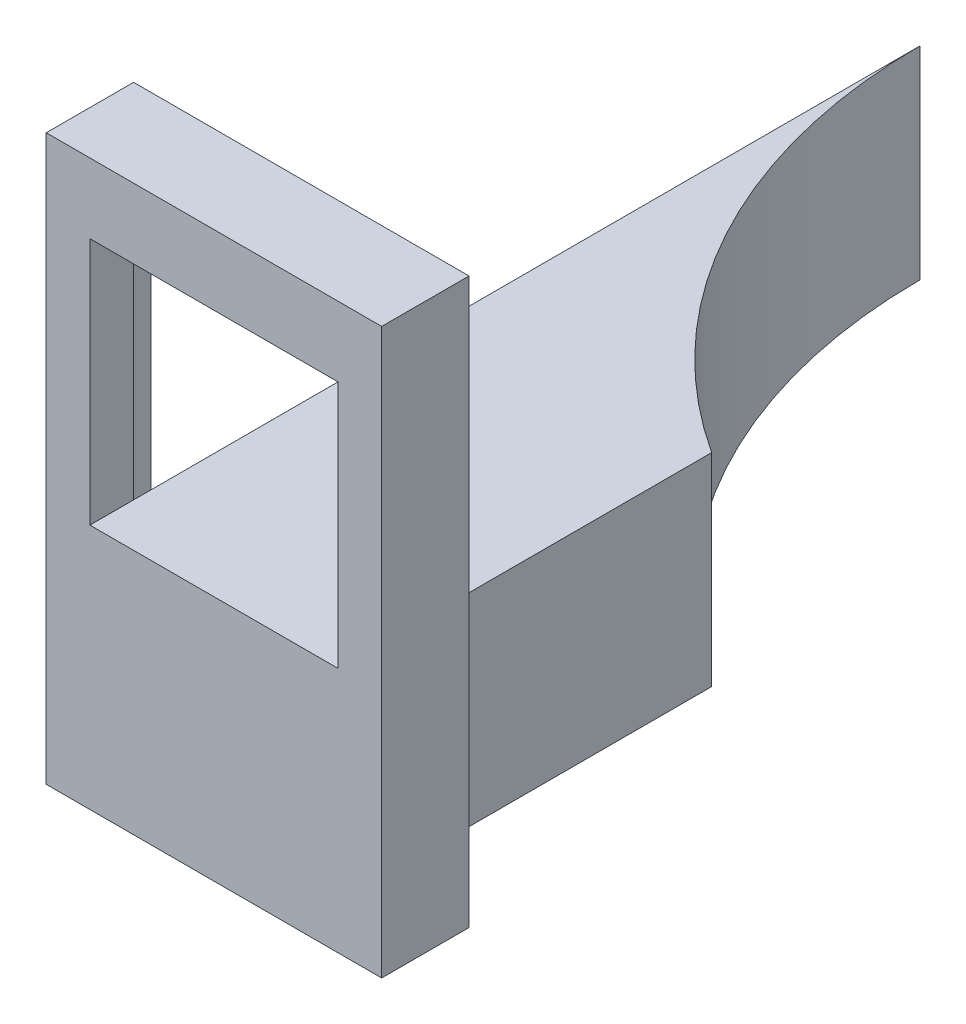
SolidWorks part; units mm, degrees
ref_plane "정면" through (0, 0, 0) normal (0, 0, 1) x (1, 0, 0)
ref_plane "윗면" through (0, 0, 0) normal (0, 1, 0) x (1, 0, 0)
ref_plane "우측면" through (0, 0, 0) normal (1, 0, 0) x (0, 0, -1)
sketch "스케치8" plane through (0, 0, 0) normal (0, 0, 1) x (1, 0, 0)
  line L0 (0, 60.6) -> (0, 0)
  line L1 (0, 0) -> (34.4, 0)
  line L2 (34.4, 0) -> (34.4, 60.6)
  line L3 (34.4, 60.6) -> (0, 60.6)
  line L4 (3, 54.6) -> (3, 3)
  line L5 (3, 3) -> (31.4, 3)
  line L6 (31.4, 3) -> (31.4, 54.6)
  line L7 (31.4, 54.6) -> (3, 54.6)
  dimension "D1" = 6
  dimension "D2" = 3
  dimension "D3" = 3
  dimension "D4" = 3
  dimension "D5" = 60.6
  dimension "D6" = 34.4
extrude "보스-돌출4" add sketch "스케치8" against normal blind 5
sketch "스케치9" plane through (0, 0, 0) normal (0, 0, 1) x (1, 0, 0)
  line L0 (31.4, 3) -> (31.4, 54.6) construction
  line L1 (3, 3) -> (31.4, 3)
  line L2 (3, 3) -> (3, 26.2)
  line L3 (3, 26.2) -> (31.4, 26.2)
  line L4 (31.4, 3) -> (31.4, 26.2)
  line L5 (31.4, 54.6) -> (3, 54.6) construction
  dimension "D1" = 28.4
extrude "보스-돌출5" add sketch "스케치9" against normal blind 95
sketch "스케치10" plane through (0, 26.2, 0) normal (0, 1, 0) x (1, 0, 0)
  circle A0 centre (65.2, 95) radius 62.2
  dimension "D1" = 124.4
extrude "컷-돌출3" cut sketch "스케치10" against normal blind 100
ref_plane "평면1" through (31.4, 26.2, -42.7851) normal (0, 0, 1) x (1, 0, 0)
sketch "스케치13" plane through (0, 0, 0) normal (0, 0, 1) x (1, 0, 0)
  line L0 (0, 60.6) -> (0, 0) construction
  line L1 (-2, -2) -> (36.4, -2)
  line L2 (-2, -2) -> (-2, 62.6)
  line L3 (-2, 62.6) -> (36.4, 62.6)
  line L4 (36.4, -2) -> (36.4, 62.6)
  line L5 (34.4, 0) -> (34.4, 60.6) construction
  line L6 (34.4, 60.6) -> (0, 60.6) construction
  line L7 (0, 0) -> (34.4, 0) construction
  line L8 (0, 0) -> (34.4, 0)
  line L9 (34.4, 0) -> (34.4, 60.6)
  line L10 (0, 60.6) -> (0, 0)
  line L11 (34.4, 60.6) -> (0, 60.6)
  dimension "D1" = 2
  dimension "D2" = 2
  dimension "D3" = 2
  dimension "D4" = 2
extrude "보스-돌출7" add sketch "스케치13" against normal blind 10
